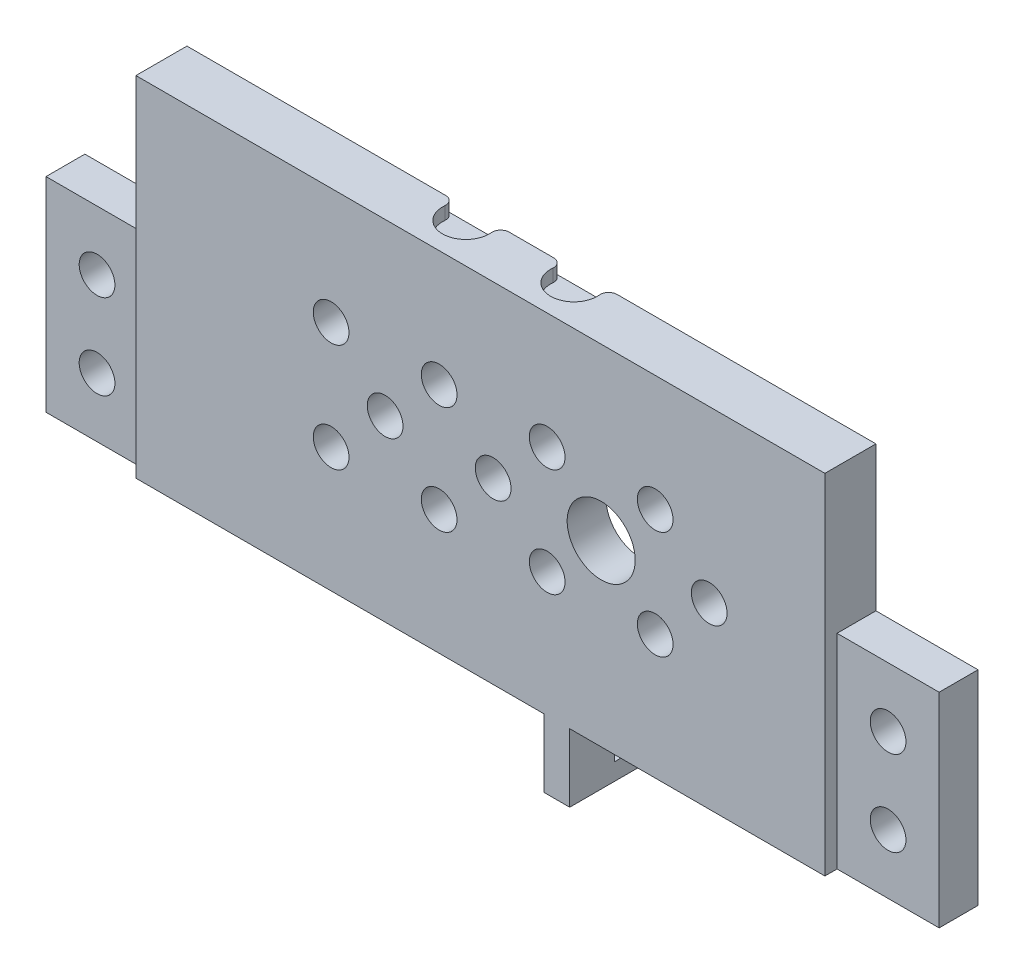
SolidWorks part; units mm, degrees
ref_plane "Front Plane" through (0, 0, 0) normal (0, 0, 1) x (1, 0, 0)
ref_plane "Top Plane" through (0, 0, 0) normal (0, 1, 0) x (1, 0, 0)
ref_plane "Right Plane" through (0, 0, 0) normal (1, 0, 0) x (0, 0, -1)
sketch "Sketch1" plane through (0, 0, 0) normal (0, 0, 1) x (1, 0, 0)
  line L1 (-40.5, -20.5) -> (40.5, -20.5)
  line L2 (-40.5, -20.5) -> (-40.5, 20.5)
  line L3 (-40.5, 20.5) -> (40.5, 20.5)
  line L4 (40.5, -20.5) -> (40.5, 20.5)
  line L5 (-40.5, -20.5) -> (40.5, 20.5) construction
  line L6 (-40.5, 20.5) -> (40.5, -20.5) construction
  point P0 (0, 0)
  dimension "D1" = 81
  dimension "D2" = 41
extrude "Boss-Extrude1" add sketch "Sketch1" along normal blind 6
sketch "Sketch5" plane through (0, 0, 0) normal (0, 0, -1) x (-1, 0, 0)
  line L1 (-37.5, -17.5) -> (37.5, -17.5)
  line L2 (-37.5, -17.5) -> (-37.5, 17.5)
  line L3 (-37.5, 17.5) -> (37.5, 17.5)
  line L4 (37.5, -17.5) -> (37.5, 17.5)
  line L5 (-37.5, -17.5) -> (37.5, 17.5) construction
  line L6 (-37.5, 17.5) -> (37.5, -17.5) construction
  point P0 (0, 0)
  dimension "D1" = 75
  dimension "D2" = 35
extrude "Cut-Extrude1" cut sketch "Sketch5" against normal blind 1.43
sketch "Sketch7" plane through (0, 0, 1.43) normal (0, 0, -1) x (-1, 0, 0)
  line L0 (37.5, 17.5) -> (-37.5, 17.5) construction
  line L1 (37.5, 17.5) -> (-37.5, 17.5) construction
  line L3 (37.5, -17.5) -> (37.5, 17.5) construction
  line L4 (-37.5, 17.5) -> (-37.5, -17.5) construction
  circle A0 centre (-14.2, 0.5) radius 2
  circle A1 centre (14.2, 0.5) radius 2
  dimension "D5" = 4
  dimension "D6" = 4
  dimension "D1" = 17
  dimension "D2" = 17
  dimension "D3" = 23.3
  dimension "D4" = 23.3
sketch "Sketch8" plane through (0, 0, 6) normal (0, 0, 1) x (1, 0, 0)
  circle A1 centre (26.9, 0.5) radius 2.1
  circle A2 centre (20.55, 6.8496) radius 2.1
  circle A3 centre (7.85, 6.8496) radius 2.1
  circle A4 centre (7.85, -5.8496) radius 2.1
  circle A5 centre (20.55, -5.8496) radius 2.1
  circle A6 centre (1.5, 0.5) radius 2.1
  circle A7 centre (-4.85, 6.8496) radius 2.1
  circle A8 centre (-4.85, -5.8496) radius 2.1
  circle A9 centre (-11.2, 0.5) radius 2.1
  circle A10 centre (-17.55, 6.8496) radius 2.1
  circle A11 centre (-17.55, -5.8496) radius 2.1
  circle A12 centre (14.2, 0.5) radius 4
  dimension "D2" = 4.2
  dimension "D3" = 4.2
  dimension "D4" = 4.2
  dimension "D5" = 4.2
  dimension "D6" = 4.2
  dimension "D7" = 4.2
  dimension "D8" = 4.2
  dimension "D9" = 4.2
  dimension "D10" = 4.2
  dimension "D11" = 4.2
  dimension "D16" = 4.2
  dimension "D20" = 8.98
  dimension "D12" = 8
  dimension "D14" = 8.98
  dimension "D15" = 8.98
  dimension "D17" = 8.98
  dimension "D19" = 8.98
  dimension "D21" = 8.98
  dimension "D22" = 8.98
  dimension "D23" = 12.7
  dimension "D24" = 12.7
extrude "Cut-Extrude2" cut sketch "Sketch8" against normal through all
sketch "Sketch9" plane through (0, 20.5, 0) normal (0, 1, 0) x (1, 0, 0)
  line L0 (0, 0) -> (12.55, 0)
  line L1 (40.5, 0) -> (-40.5, 0) construction
  line L2 (0, 0) -> (-12.55, 0)
  line L5 (-6.35, 0) -> (-6.35, -1.35)
  line L6 (6.35, 0) -> (6.35, -1.35)
  circle A4 centre (6.35, -1.35) radius 2.75
  circle A5 centre (-6.35, -1.35) radius 2.75
  dimension "D3" = 5.5
  dimension "D4" = 5.5
  dimension "D1" = 12.55
  dimension "D2" = 12.55
  dimension "D6" = 6.2
  dimension "D9" = 1.35
  dimension "D10" = 1.35
extrude "Cut-Extrude3" cut sketch "Sketch9" against normal blind 1.5
fillet "Fillet1" radius 1 4 edges at (8.7458, 19.75, 0) (3.9542, 19.75, 0) (-8.7458, 19.75, 0) (-3.9542, 19.75, 0)
sketch "Sketch10" plane through (-40.5, 0, 0) normal (-1, 0, 0) x (0, 0, 1)
  line L1 (0, -20.5) -> (4.57, -20.5)
  line L2 (0, -20.5) -> (0, 3.5)
  line L3 (0, 3.5) -> (4.57, 3.5)
  line L4 (4.57, -20.5) -> (4.57, 3.5)
  dimension "D1" = 24
  dimension "D2" = 4.57
extrude "Boss-Extrude2" add sketch "Sketch10" along normal blind 12
sketch "Sketch12" plane through (40.5, 0, 0) normal (1, 0, 0) x (0, 0, -1)
  line L1 (0, -20.5) -> (-4.57, -20.5)
  line L2 (0, -20.5) -> (0, 3.5)
  line L3 (0, 3.5) -> (-4.57, 3.5)
  line L4 (-4.57, -20.5) -> (-4.57, 3.5)
  dimension "D1" = 24
  dimension "D2" = 4.57
extrude "Boss-Extrude3" add sketch "Sketch12" along normal blind 12
sketch "Sketch13" plane through (0, 0, 4.57) normal (0, 0, 1) x (1, 0, 0)
  line L0 (-46.5, 3.5) -> (-46.5, -6.4) construction
  line L1 (-52.5, 3.5) -> (-40.5, 3.5) construction
  line L2 (-52.5, -20.5) -> (-40.5, -20.5) construction
  line L3 (46.5, 3.5) -> (46.5, -6.4) construction
  line L4 (52.5, 3.5) -> (40.5, 3.5) construction
  line L5 (52.5, -20.5) -> (40.5, -20.5) construction
  line L6 (-46.5, -10.6) -> (-46.5, -20.5) construction
  line L7 (46.5, -10.6) -> (46.5, -20.5) construction
  circle A1 centre (-46.5, -3.5) radius 2.1
  circle A2 centre (-46.5, -13.5) radius 2.1
  circle A4 centre (46.5, -3.5) radius 2.1
  circle A5 centre (46.5, -13.5) radius 2.1
  dimension "D1" = 4.2
  dimension "D2" = 7
  dimension "D3" = 4.2
  dimension "D4" = 4.2
  dimension "D5" = 7
  dimension "D6" = 4.2
  dimension "D7" = 7
  dimension "D8" = 7
extrude "Cut-Extrude4" cut sketch "Sketch13" against normal through all
sketch "Sketch14" plane through (0, -20.5, 0) normal (0, -1, 0) x (1, 0, 0)
  line L0 (0, 0) -> (7.5, 0)
  line L2 (-52.5, 0) -> (52.5, 0) construction
  line L3 (7.5, 0) -> (7.5, 6)
  line L4 (-40.5, 6) -> (40.5, 6) construction
  line L6 (7.5, 6) -> (10.5, 6)
  line L7 (7.5, 6) -> (7.5, -15)
  line L8 (7.5, -15) -> (10.5, -15)
  line L9 (10.5, 6) -> (10.5, -15)
  line M5 (-52.5, 0) -> (52.5, 0)
  line M9 (40.5, 6) -> (-40.5, 6)
  dimension "D1" = 7.5
  dimension "D2" = 3
  dimension "D3" = 21
extrude "Boss-Extrude4" add sketch "Sketch14" along normal blind 8 contours L9 L7 L8 M5 | L9 L3 M9 M5
sketch "Sketch15" plane through (10.5, 0, 0) normal (1, 0, 0) x (0, 0, -1)
  line L0 (15, -28.5) -> (-6, -20.5) construction
  line L1 (-6, -28.5) -> (15, -20.5) construction
  line L3 (-0.75, -22.5) -> (9.75, -22.5)
  line L4 (-0.75, -22.5) -> (-0.75, -26.5)
  line L5 (-0.75, -26.5) -> (9.75, -26.5)
  line L6 (9.75, -22.5) -> (9.75, -26.5)
  line L7 (-0.75, -22.5) -> (9.75, -26.5) construction
  line L8 (-0.75, -26.5) -> (9.75, -22.5) construction
  point P8 (4.5, -24.5)
  dimension "D1" = 4
extrude "Cut-Extrude5" cut sketch "Sketch15" against normal through all
